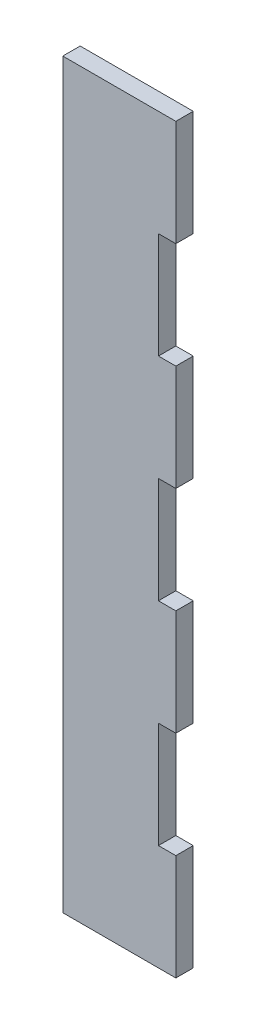
SolidWorks part; units mm, degrees
ref_plane "Front Plane" through (0, 0, 0) normal (0, 0, 1) x (1, 0, 0)
ref_plane "Top Plane" through (0, 0, 0) normal (0, 1, 0) x (1, 0, 0)
ref_plane "Right Plane" through (0, 0, 0) normal (1, 0, 0) x (0, 0, -1)
sketch "Sketch1" plane through (0, 0, 0) normal (0, 0, 1) x (1, 0, 0)
  line L0 (0, 101.6) -> (0, -101.6) construction
  line L1 (-6.35, 101.6) -> (6.35, 101.6)
  line L2 (-6.35, 101.6) -> (-6.35, -101.6)
  line L3 (-6.35, -101.6) -> (6.35, -101.6)
  line L4 (6.35, 101.6) -> (6.35, -101.6)
  line L5 (6.35, 72.5714) -> (6.35, 43.5429)
  line L6 (6.35, 101.6) -> (11.1125, 101.6)
  line L7 (6.35, 101.6) -> (6.35, 72.5714)
  line L8 (6.35, 72.5714) -> (11.1125, 72.5714)
  line L9 (11.1125, 101.6) -> (11.1125, 72.5714)
  line L10 (6.35, 72.5714) -> (11.1125, 72.5714)
  line L11 (11.1125, 72.5714) -> (11.1125, 43.5429)
  line L12 (6.35, 43.5429) -> (11.1125, 43.5429)
  line L13 (6.35, 43.5429) -> (6.35, 14.5143)
  line L14 (6.35, 43.5429) -> (11.1125, 43.5429)
  line L15 (11.1125, 43.5429) -> (11.1125, 14.5143)
  line L16 (6.35, 14.5143) -> (11.1125, 14.5143)
  line L17 (6.35, 14.5143) -> (6.35, -14.5143)
  line L18 (6.35, 14.5143) -> (11.1125, 14.5143)
  line L19 (11.1125, 14.5143) -> (11.1125, -14.5143)
  line L20 (6.35, -14.5143) -> (11.1125, -14.5143)
  line L21 (6.35, -14.5143) -> (6.35, -43.5429)
  line L22 (6.35, -14.5143) -> (11.1125, -14.5143)
  line L23 (11.1125, -14.5143) -> (11.1125, -43.5429)
  line L24 (6.35, -43.5429) -> (11.1125, -43.5429)
  line L25 (6.35, -43.5429) -> (6.35, -72.5714)
  line L26 (6.35, -43.5429) -> (11.1125, -43.5429)
  line L27 (11.1125, -43.5429) -> (11.1125, -72.5714)
  line L28 (6.35, -72.5714) -> (11.1125, -72.5714)
  line L29 (6.35, -72.5714) -> (6.35, -101.6)
  line L30 (6.35, -72.5714) -> (11.1125, -72.5714)
  line L31 (11.1125, -72.5714) -> (11.1125, -101.6)
  line L32 (6.35, -101.6) -> (11.1125, -101.6)
  point P6 (0, 0)
  dimension "D2" = 12.7
  dimension "D1" = 203.2
  dimension "D3" = 29.0286
  dimension "D4" = 4.7625
  dimension "D5" = 7
extrude "Boss-Extrude1" add sketch "Sketch1" along normal blind 4.7625 contours L0 L1 L2 L3 | L1 L0 L3 L4 | L9 L6 L4 L8 | L4 L16 L15 L12 | L4 L24 L23 L20 | L4 L32 L31 L28
sketch "Sketch2" plane through (-6.35, 0, 0) normal (-1, 0, 0) x (0, 0, 1)
  line L1 (4.7625, -101.6) -> (0, -101.6)
  line L2 (4.7625, -101.6) -> (4.7625, 101.6)
  line L3 (4.7625, 101.6) -> (0, 101.6)
  line L4 (0, -101.6) -> (0, 101.6)
extrude "Boss-Extrude2" add sketch "Sketch2" along normal blind 13.5
equation "\"Height\"= 12in"
equation "\"Depth\"= 7in"
equation "\"WallThickness\"= 0.1875in"
equation "\"FloorThickness\"= 0.1875in"
equation "\"Width\"= 30in"
equation "\"D1@Boss-Extrude1\"=\"WallThickness\""
equation "\"D3@Sketch1\"=\"D1@Sketch1\"/\"D5@Sketch1\""
equation "\"D4@Sketch1\"=\"WallThickness\""
